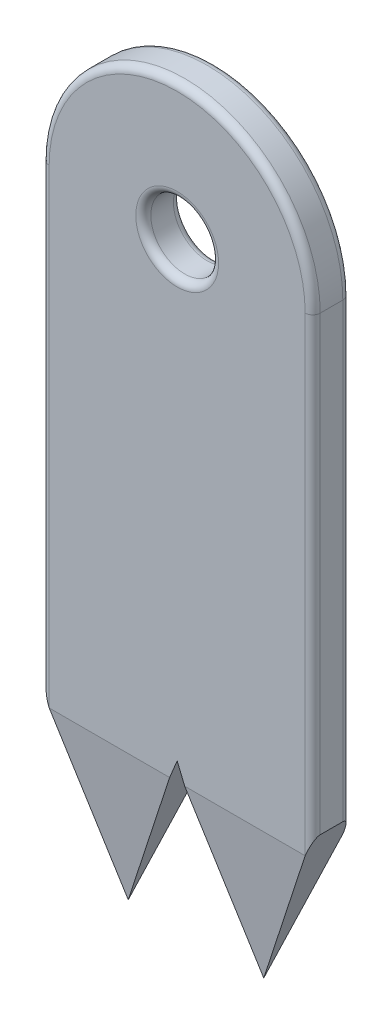
SolidWorks part; units mm, degrees
ref_plane "Front Plane" through (0, 0, 0) normal (0, 0, 1) x (1, 0, 0)
ref_plane "Top Plane" through (0, 0, 0) normal (0, 1, 0) x (1, 0, 0)
ref_plane "Right Plane" through (0, 0, 0) normal (1, 0, 0) x (0, 0, -1)
sketch "Sketch1" plane through (0, 0, 0) normal (0, 0, 1) x (1, 0, 0)
  line L0 (-21.7589, -29.1627) -> (-30.7589, -7.4348)
  line L2 (-12.7589, -7.4348) -> (-21.7589, -29.1627)
  line L3 (-12.7589, -7.4348) -> (-3.7589, -29.1627)
  line L4 (-3.7589, -29.1627) -> (5.2411, -7.4348)
  line L6 (-30.7589, -7.4348) -> (-30.7589, 52.5652)
  line L8 (5.2411, 52.5652) -> (5.2411, -7.4348)
  arc A0 (5.2411, 52.5652) -> (-30.7589, 52.5652) centre (-12.7589, 52.5652) ccw
  circle A1 centre (-12.7589, 52.5652) radius 4.5
  dimension "D5" = 9
  dimension "D6" = 18
  dimension "D1" = 18
  dimension "D2" = 18
  dimension "D3" = 21.7279
  dimension "D4" = 45
  dimension "D7" = 60
extrude "Boss-Extrude1" add sketch "Sketch1" along normal blind 5
fillet "Fillet1" radius 1 8 edges at (5.2411, 22.5652, 0) (-30.7589, 22.5652, 0) (5.2411, 22.5652, 5) (-30.7589, 22.5652, 5) (-12.7589, 70.5652, 0) (-12.7589, 70.5652, 5) (-8.2589, 52.5652, 0) (-8.2589, 52.5652, 5)
sketch "Sketch5" plane through (0, 0, 0) normal (1, 0, 0) x (0, 0, -1)
  line L1 (0, -9.849) -> (-2.5, -29.1627)
  line L2 (-5, -29.1627) -> (0, -29.1627) construction
  line L3 (-2.5, -29.1627) -> (-5, -9.849)
  line L4 (-5, -9.849) -> (-5, -29.1627)
  line L6 (0, -29.1627) -> (0, -9.849)
  line L7 (-5, -29.1627) -> (-2.5, -29.1627)
  line L8 (-2.5, -29.1627) -> (0, -29.1627)
  point P4 (0, 0)
  point P12 (0, 0)
  point P13 (0, -29.1627)
  point P14 (0, 0)
extrude "Cut-Extrude1" cut sketch "Sketch5" against normal through all both and the other way through all contours L3 L4 L7
sketch "Sketch9" plane through (5.2411, 0, 0) normal (1, 0, 0) x (0, 0, -1)
  line L0 (-2.5, -7.4348) -> (-2.5, -38.782) construction
  line L1 (-4, -7.4348) -> (-1, -7.4348) construction
  line L2 (-2.5, -29.1627) -> (0, -9.849)
  line L3 (-2.5, -29.1627) -> (0, -29.1627)
  line L4 (0, -29.1627) -> (0, -9.849)
extrude "Cut-Extrude3" cut sketch "Sketch9" against normal through all both
